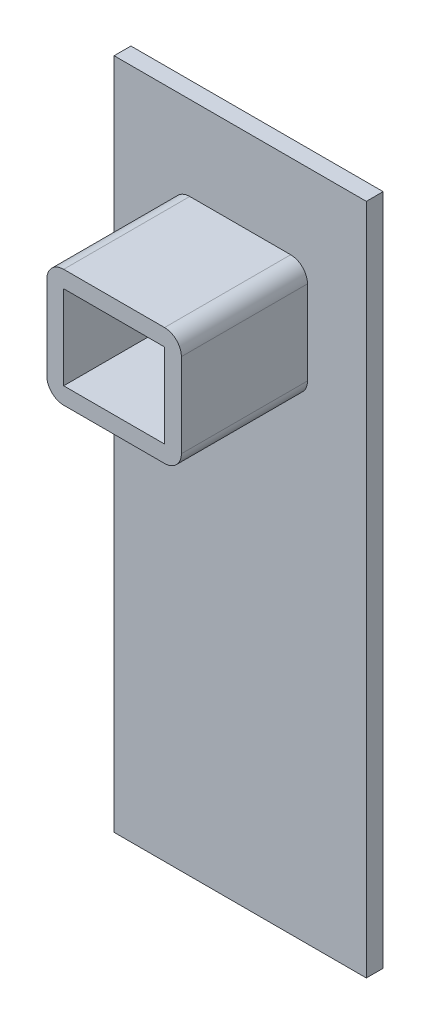
SolidWorks part; units mm, degrees
ref_plane "前视基准面" through (0, 0, 0) normal (0, 0, 1) x (1, 0, 0)
ref_plane "上视基准面" through (0, 0, 0) normal (0, 1, 0) x (1, 0, 0)
ref_plane "右视基准面" through (0, 0, 0) normal (1, 0, 0) x (0, 0, -1)
sketch "草图1" plane through (0, 0, 0) normal (0, 0, 1) x (1, 0, 0)
  line L1 (0, 0) -> (30, 0)
  line L2 (0, 0) -> (0, -80)
  line L3 (0, -80) -> (30, -80)
  line L4 (30, 0) -> (30, -80)
extrude "凸台-拉伸1" add sketch "草图1" along normal blind 2
sketch "草图2" plane through (0, 0, 2) normal (0, 0, 1) x (1, 0, 0)
  line L0 (15, 0) -> (15, -80) construction
  line L1 (30, 0) -> (0, 0) construction
  line L2 (0, -80) -> (30, -80) construction
  line L4 (15, -10) -> (23, -10)
  line L5 (23, -10) -> (23, -24)
  line L6 (23, -24) -> (7, -24)
  line L7 (7, -24) -> (7, -10)
  line L8 (7, -10) -> (15, -10)
  line L9 (15, -12) -> (21, -12)
  line L10 (21, -12) -> (21, -22)
  line L11 (21, -22) -> (9, -22)
  line L12 (9, -22) -> (9, -12)
  line L13 (9, -12) -> (15, -12)
extrude "凸台-拉伸2" add sketch "草图2" along normal blind 15
fillet "圆角1" radius 2 4 edges at (7, -10, 9.5) (7, -24, 9.5) (23, -24, 9.5) (23, -10, 9.5)
sketch "草图4" plane through (0, 0, 2) normal (0, 0, 1) x (1, 0, 0)
  line L0 (15, -80) -> (15, 0)
  line L1 (0, -80) -> (30, -80) construction
  line L2 (30, 0) -> (0, 0) construction
